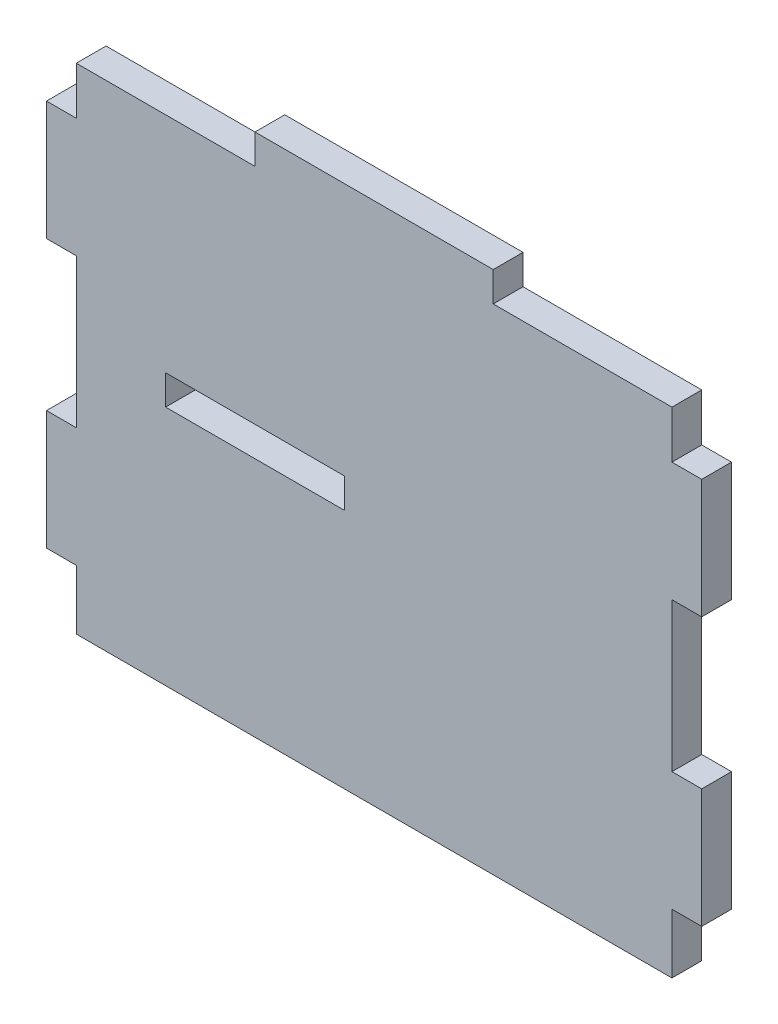
SolidWorks part; units mm, degrees
ref_plane "前视基准面" through (0, 0, 0) normal (0, 0, 1) x (1, 0, 0)
ref_plane "上视基准面" through (0, 0, 0) normal (0, 1, 0) x (1, 0, 0)
ref_plane "右视基准面" through (0, 0, 0) normal (1, 0, 0) x (0, 0, -1)
sketch "草图1" plane through (0, 0, 0) normal (0, 0, 1) x (1, 0, 0)
  line L0 (0, 75) -> (0, 83)
  line L1 (0, 0) -> (100, 0)
  line L2 (0, 0) -> (0, 10)
  line L3 (0, 83) -> (30, 83)
  line L4 (100, 0) -> (100, 10)
  line L5 (15, 45.5) -> (45, 45.5)
  line L6 (15, 45.5) -> (15, 40.5)
  line L7 (15, 40.5) -> (45, 40.5)
  line L8 (45, 45.5) -> (45, 40.5)
  line L9 (0, 10) -> (-5, 10)
  line L11 (0, 30) -> (-5, 30)
  line L12 (-5, 10) -> (-5, 30)
  line L13 (0, 75) -> (-5, 75)
  line L15 (0, 55) -> (-5, 55)
  line L16 (-5, 75) -> (-5, 55)
  line L17 (100, 75) -> (105, 75)
  line L19 (100, 55) -> (105, 55)
  line L20 (105, 75) -> (105, 55)
  line L21 (100, 30) -> (105, 30)
  line L23 (100, 10) -> (105, 10)
  line L24 (105, 30) -> (105, 10)
  line L26 (30, 83) -> (30, 88)
  line L27 (30, 88) -> (70, 88)
  line L28 (70, 83) -> (70, 88)
  line L29 (0, 30) -> (0, 55)
  line L30 (100, 30) -> (100, 55)
  line L31 (100, 75) -> (100, 83)
  line L32 (70, 83) -> (100, 83)
  point P17 (-2.5, 75)
  dimension "D1" = 83
  dimension "D2" = 100
  dimension "D3" = 30
  dimension "D4" = 5
  dimension "D5" = 15
  dimension "D6" = 40.5
  dimension "D7" = 20
  dimension "D8" = 20
  dimension "D9" = 5
  dimension "D10" = 5
  dimension "D11" = 8
  dimension "D12" = 10
  dimension "D13" = 20
  dimension "D14" = 5
  dimension "D15" = 5
  dimension "D16" = 20
  dimension "D17" = 8
  dimension "D18" = 10
  dimension "D19" = 40
  dimension "D20" = 5
  dimension "D21" = 30
extrude "凸台-拉伸1" add sketch "草图1" along normal blind 5
